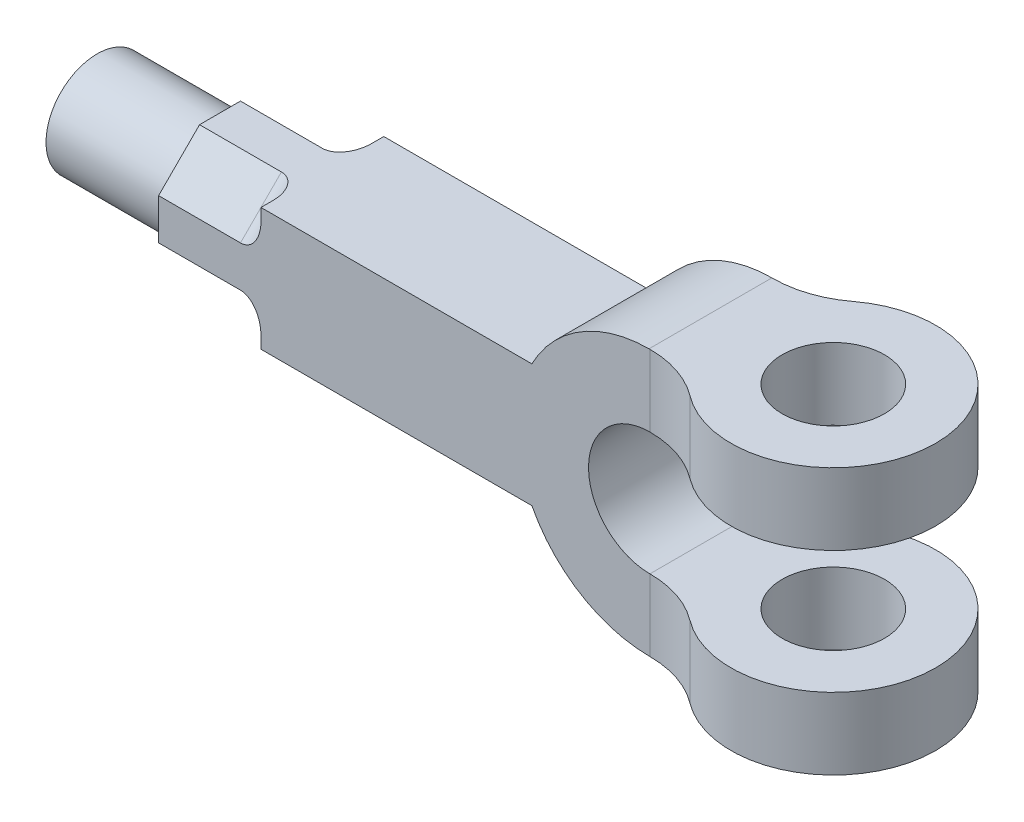
SolidWorks part; units mm, degrees
ref_plane "Front Plane" through (0, 0, 0) normal (0, 0, 1) x (1, 0, 0)
ref_plane "Top Plane" through (0, 0, 0) normal (0, 1, 0) x (1, 0, 0)
ref_plane "Right Plane" through (0, 0, 0) normal (1, 0, 0) x (0, 0, -1)
sketch "Sketch1" plane through (0, 0, 0) normal (0, 1, 0) x (1, 0, 0)
  line L1 (-24, 12) -> (-24, -12)
  line L2 (-24, 12) -> (-23.8328, 12)
  line L3 (-24, -12) -> (-23.8328, -12)
  arc A0 (-12.0672, -15.9494) -> (-12.0672, 15.9494) centre (0, 0) ccw
  arc A1 (-12.0672, -15.9494) -> (-23.8328, -12) centre (-23.8328, -31.5) ccw
  arc A2 (-12.0672, 15.9494) -> (-23.8328, 12) centre (-23.8328, 31.5) cw
  point P7 (-24, 0)
  dimension "D1" = 19.5
extrude "Boss-Extrude1" add sketch "Sketch1" along normal blind 14
sketch "Sketch3" plane through (0, 0, 0) normal (0, 0, 1) x (1, 0, 0)
  line L0 (-46.8979, 0) -> (-119.8328, 0)
  line L1 (-23.8328, -24) -> (-23.8328, -38)
  line L2 (-46.8979, -24) -> (-119.8328, -24)
  line L3 (-119.8328, -24) -> (-119.8328, 0)
  line L4 (-23.8328, 0) -> (-23.8328, 14)
  arc A0 (-23.8328, 0) -> (-23.8328, -24) centre (-23.8328, -12) ccw
  arc A1 (-23.8328, 14) -> (-46.8979, 0) centre (-23.8328, -12) ccw
  arc A2 (-46.8979, -24) -> (-23.8328, -38) centre (-23.8328, -12) ccw
extrude "Boss-Extrude2" add sketch "Sketch3" along normal blind 12 and the other way blind 12
sketch "Sketch4" plane through (-119.8328, 0, 0) normal (-1, 0, 0) x (0, 0, 1)
  line L0 (-12, 0) -> (-4, 0)
  line L1 (-12, 0) -> (12, 0) construction
  line L2 (-12, 0) -> (-12, -8)
  line L3 (-12, 0) -> (-12, -24) construction
  line L4 (-12, -8) -> (-4, 0)
  line L5 (4, 0) -> (12, -8)
  line L6 (12, 0) -> (12, -8)
  line L7 (12, 0) -> (4, 0)
  line L8 (12, -16) -> (4, -24)
  line L9 (12, -24) -> (4, -24)
  line L10 (12, -24) -> (12, -16)
  line L11 (-4, -24) -> (-12, -16)
  line L12 (-12, -24) -> (-12, -16)
  line L13 (-12, -24) -> (-4, -24)
  point P13 (0, -12)
  point P21 (0, -12)
  dimension "D1" = 4
extrude "Cut-Extrude1" cut sketch "Sketch4" against normal blind 20
fillet "Fillet1" radius 4 4 edges at (-99.8328, -4, 8) (-99.8328, -20, 8) (-99.8328, -20, -8) (-99.8328, -4, -8)
sketch "Sketch5" plane through (-119.8328, 0, 0) normal (-1, 0, 0) x (0, 0, 1)
  circle A0 centre (0, -12) radius 10
extrude "Boss-Extrude3" add sketch "Sketch5" along normal blind 24
ref_plane "Plane1" through (0, -12, 0) normal (0, 1, 0) x (1, 0, 0)
mirror "Mirror1" about plane through (0, -12, 0) normal (0, 1, 0) of "Boss-Extrude1"
sketch "Sketch6" plane through (0, 14, 0) normal (0, 1, 0) x (1, 0, 0)
  circle A0 centre (0, 0) radius 10
extrude "Cut-Extrude2" cut sketch "Sketch6" against normal blind 78
